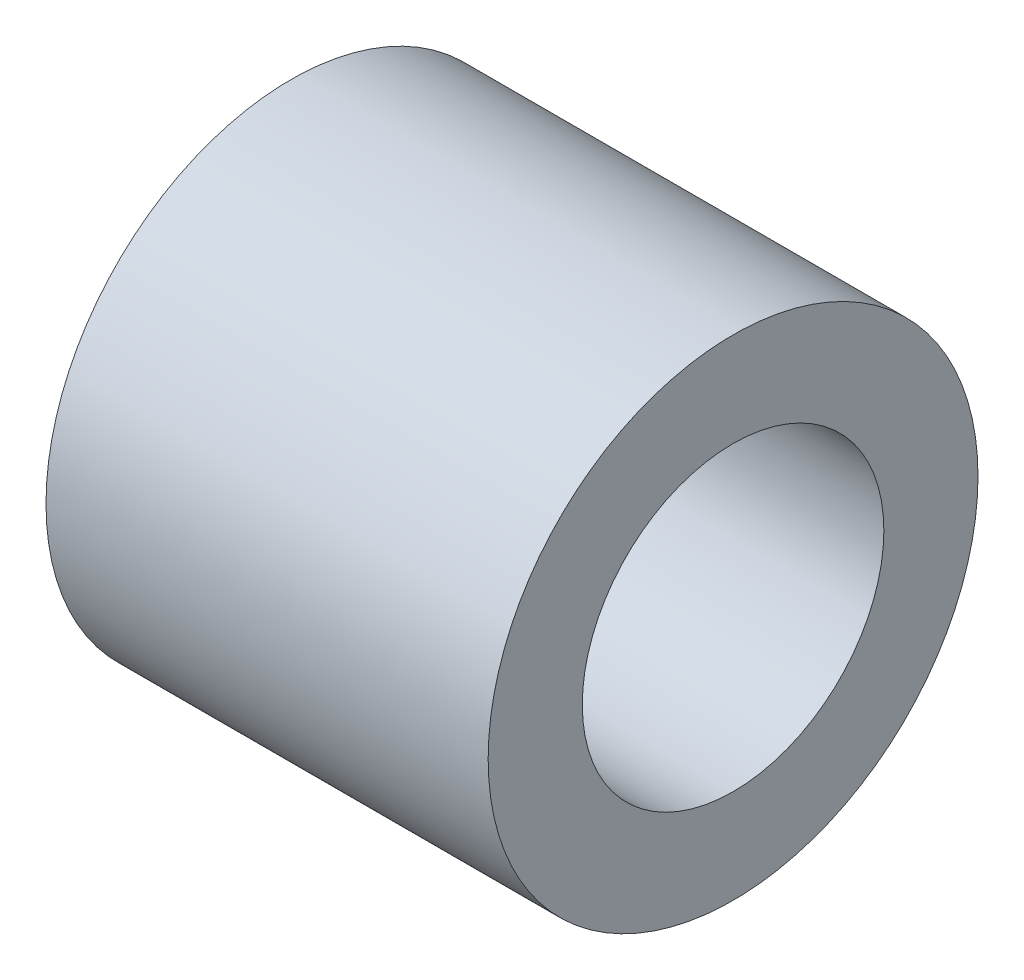
SolidWorks part; units mm, degrees
material "PE High Density"
ref_plane "Front Plane" through (0, 0, 0) normal (0, 0, 1) x (1, 0, 0)
ref_plane "Top Plane" through (0, 0, 0) normal (0, 1, 0) x (1, 0, 0)
ref_plane "Right Plane" through (0, 0, 0) normal (1, 0, 0) x (0, 0, -1)
sketch "Sketch1" plane through (0, 0, 0) normal (1, 0, 0) x (0, 0, -1)
  circle A0 centre (0, 0) radius 4.93
  circle A1 centre (0, 0) radius 3.035
  dimension "D1" = 9.86
  dimension "D2" = 6.07
extrude "Boss-Extrude1" add sketch "Sketch1" along normal mid plane 8.9 contours A0
